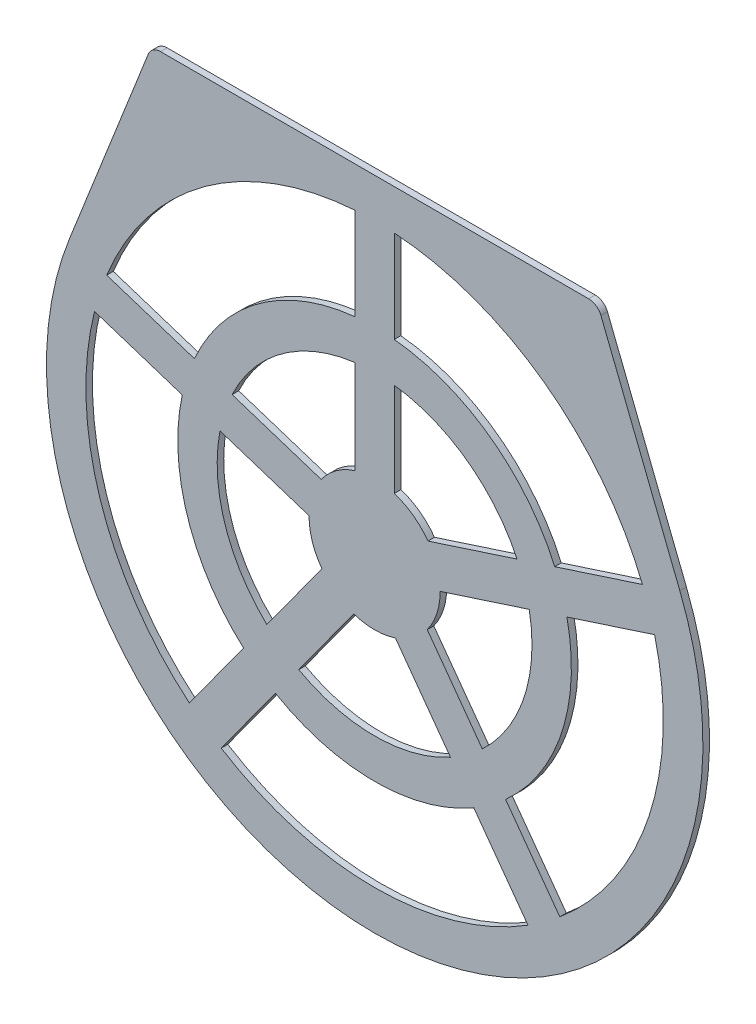
SolidWorks part; units mm, degrees
ref_plane "Front Plane" through (0, 0, 0) normal (0, 0, 1) x (1, 0, 0)
ref_plane "Top Plane" through (0, 0, 0) normal (0, 1, 0) x (1, 0, 0)
ref_plane "Right Plane" through (0, 0, 0) normal (1, 0, 0) x (0, 0, -1)
sketch "Sketch1" plane through (0, 0, 0) normal (0, 0, 1) x (1, 0, 0)
  line L0 (-232.3777, 91.9463) -> (-172.367, 243.6779)
  line L1 (172.3709, 243.688) -> (232.4769, 92.2007)
  line L2 (169.8665, 240) -> (169.8665, 250) construction
  line L3 (159.8665, 250) -> (173.1048, 250) construction
  line L4 (-169.8665, 240) -> (-169.8665, 269.4488) construction
  line L5 (-159.8665, 250) -> (-169.8665, 250) construction
  line L6 (-163.0679, 250) -> (-0.1, 250)
  line L7 (0.1, 279.9426) -> (0.1, 364.1749) construction
  line L9 (0, 0) -> (266.2413, 86.507) construction
  line L12 (-0.1, 250) -> (163.0759, 250)
  line L13 (0, 0) -> (164.5462, -226.4784) construction
  line L14 (0, 0) -> (-164.5462, -226.4784) construction
  line L15 (0, 0) -> (-266.2413, 86.507) construction
  line L17 (15.8387, -47.3196) -> (57.7865, -105.0558)
  line L18 (-40.1092, -29.6861) -> (-82.057, -87.4223)
  line L23 (40.1092, -29.6861) -> (82.057, -87.4223)
  line L25 (-49.8981, 0.4409) -> (-117.7711, 22.4942)
  line L26 (-137.2126, 60.355) -> (-204.0149, 82.0604)
  line L29 (12.1353, 8.8168) -> (176.6814, -217.6616) construction
  line L33 (-4.6353, -14.2658) -> (-270.8765, 72.2412) construction
  line L35 (-146.4831, 31.8233) -> (-213.2855, 53.5287)
  line L36 (-99.802, -111.8462) -> (-141.0882, -168.6717)
  line L37 (-75.5315, -129.4797) -> (-116.8177, -186.3052)
  line L38 (75.5315, -129.4797) -> (116.8177, -186.3052)
  line L39 (99.802, -111.8462) -> (141.0882, -168.6717)
  line L40 (146.4831, 31.8233) -> (213.2855, 53.5287)
  line L41 (137.2126, 60.355) -> (204.0149, 82.0604)
  line L42 (15, 149.1476) -> (15, 219.3878)
  line L45 (-15, 149.1476) -> (-15, 219.3878)
  line L46 (15, 47.5921) -> (15, 118.958)
  line L47 (40.6275, 28.9726) -> (108.5005, 51.0259)
  line L48 (-40.6275, 28.9726) -> (-108.5005, 51.0259)
  line L49 (-15, 47.5921) -> (-15, 118.958)
  line L50 (49.8981, 0.4409) -> (117.7711, 22.4942)
  line L51 (-15.8387, -47.3196) -> (-57.7865, -105.0558)
  arc A0 (-232.3777, 91.9463) -> (232.4769, 92.2007) centre (0.1, 0) ccw
  arc A1 (-163.0679, 250) -> (-172.367, 243.6779) centre (-163.0679, 240) ccw
  arc A2 (163.0759, 250) -> (172.3709, 243.688) centre (163.0759, 240) cw
  arc A4 (204.0149, 82.0604) -> (15, 219.3878) centre (0, 0) ccw
  arc A5 (-146.4831, 31.8233) -> (-99.802, -111.8462) centre (0, 0) ccw
  arc A6 (-117.7711, 22.4942) -> (-82.057, -87.4223) centre (0, 0) ccw
  arc A7 (40.6275, 28.9726) -> (15, 47.5921) centre (0, 0) ccw
  arc A8 (141.0882, -168.6717) -> (213.2855, 53.5287) centre (0, 0) ccw
  circle A9 centre (0, 0) radius 219.9 construction
  arc A10 (-116.8177, -186.3052) -> (116.8177, -186.3052) centre (0, 0) ccw
  arc A11 (-213.2855, 53.5287) -> (-141.0882, -168.6717) centre (0, 0) ccw
  arc A12 (-75.5315, -129.4797) -> (75.5315, -129.4797) centre (0, 0) ccw
  circle A13 centre (0, 0) radius 149.9 construction
  circle A14 centre (0, 0) radius 119.9 construction
  arc A15 (-57.7865, -105.0558) -> (57.7865, -105.0558) centre (0, 0) ccw
  arc A16 (82.057, -87.4223) -> (117.7711, 22.4942) centre (0, 0) ccw
  arc A17 (99.802, -111.8462) -> (146.4831, 31.8233) centre (0, 0) ccw
  arc A18 (137.2126, 60.355) -> (15, 149.1476) centre (0, 0) ccw
  arc A19 (108.5005, 51.0259) -> (15, 118.958) centre (0, 0) ccw
  arc A20 (-15, 219.3878) -> (-204.0149, 82.0604) centre (0, 0) ccw
  arc A23 (-15, 149.1476) -> (-137.2126, 60.355) centre (0, 0) ccw
  arc A24 (-15, 118.958) -> (-108.5005, 51.0259) centre (0, 0) ccw
  circle A27 centre (0, 0) radius 49.9 construction
  arc A28 (-15, 47.5921) -> (-40.6275, 28.9726) centre (0, 0) ccw
  arc A29 (-49.8981, 0.4409) -> (-40.1092, -29.6861) centre (0, 0) ccw
  arc A30 (-15.8387, -47.3196) -> (15.8387, -47.3196) centre (0, 0) ccw
  arc A31 (40.1092, -29.6861) -> (49.8981, 0.4409) centre (0, 0) ccw
  point P2 (15, 0)
  point P9 (15, 279.9426)
  point P21 (0, 0)
  point P35 (4.6353, -14.2658)
  point P36 (270.8765, 72.2412)
  point P37 (-12.1353, -8.8168)
  point P38 (152.4109, -235.2951)
  point P39 (-12.1353, 8.8168)
  point P40 (-176.6814, -217.6616)
  point P41 (4.6353, 14.2658)
  point P42 (-261.606, 100.7729)
  point P43 (-15, 0)
  point P44 (-15, 279.9426)
  point P45 (-4.6353, 14.2658)
  point P46 (261.606, 100.7729)
  point P49 (12.1353, -8.8168)
  point P50 (-152.4109, -235.2951)
  point P60 (219.9, 0)
  point P70 (143.3501, 43.8265)
  point P73 (114.6609, 35.0554)
  point P100 (47.7196, 14.5893)
  dimension "D1" = 500
  dimension "D4" = 10
  dimension "D7" = 15
  dimension "D8" = 70
  dimension "D9" = 30
  dimension "D10" = 70
extrude "Boss-Extrude1" add sketch "Sketch1" along normal blind 5
